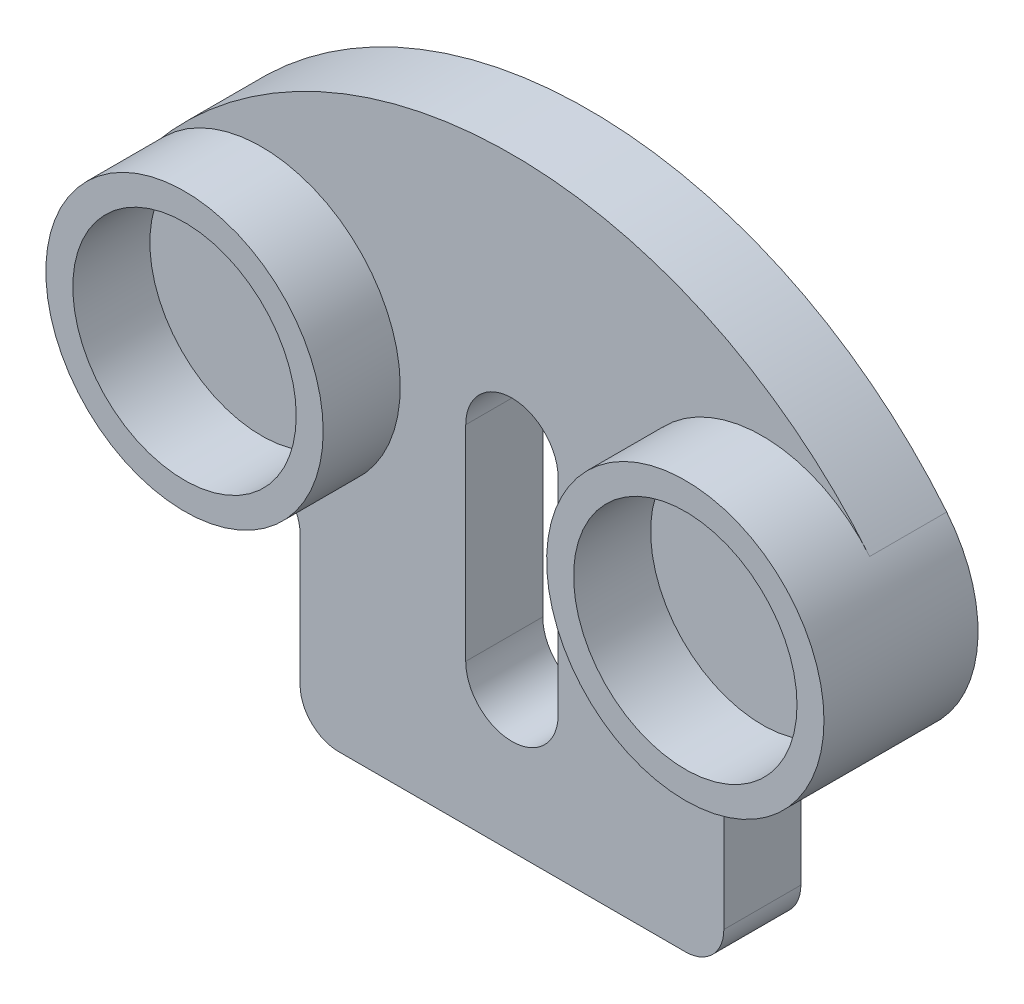
SolidWorks part; units mm, degrees
ref_plane "Płaszczyzna przednia" through (0, 0, 0) normal (0, 0, 1) x (1, 0, 0)
ref_plane "Płaszczyzna górna" through (0, 0, 0) normal (0, 1, 0) x (1, 0, 0)
ref_plane "Płaszczyzna prawa" through (0, 0, 0) normal (1, 0, 0) x (0, 0, -1)
sketch "Szkic1" plane through (0, 0, 0) normal (0, 0, 1) x (1, 0, 0)
  line L0 (-6, 26.6036) -> (-6, 0)
  line L1 (6, 26.6036) -> (6, 0)
  line L2 (-22.5, -18.3964) -> (22.5, -18.3964)
  line L3 (0, 0) -> (0, -18.3964) construction
  line L4 (-95.3968, 26.6036) -> (116.5066, 26.6036) construction
  line L5 (-27.5, -13.3964) -> (-27.5, 3.6036)
  line L6 (27.5, -13.3964) -> (27.5, 3.6036)
  circle A2 centre (0, 0) radius 6
  circle A4 centre (0, 26.6036) radius 6
  circle A5 centre (-32.5, 26.6036) radius 18
  circle A6 centre (32.5, 26.6036) radius 18
  circle A7 centre (-32.5, 26.6036) radius 13
  circle A8 centre (32.5, 26.6036) radius 13
  arc A9 (-22.5, -18.3964) -> (-27.5, -13.3964) centre (-22.5, -13.3964) cw
  arc A10 (-27.5, 3.6036) -> (-32.5, 8.6036) centre (-32.5, 3.6036) ccw
  arc A11 (22.5, -18.3964) -> (27.5, -13.3964) centre (22.5, -13.3964) ccw
  arc A12 (27.5, 3.6036) -> (32.5, 8.6036) centre (32.5, 3.6036) cw
  arc A13 (-46.4286, 38.0051) -> (46.4286, 38.0051) centre (0, 0) cw
  point P35 (0, 0)
  dimension "D3" = 45
  dimension "D4" = 65
  dimension "D2" = 12
  dimension "D6" = 36
  dimension "D7" = 32.5
  dimension "D8" = 5
  dimension "D1" = 12
  dimension "D5" = 36
  dimension "D10" = 5
  dimension "D11" = 5
  dimension "D12" = 5
  dimension "D13" = 5
  dimension "D14" = 60
  dimension "D9" = 5
  dimension "D15" = 45
extrude "Dodanie-wyciągnięcie5" add sketch "Szkic1" along normal blind 20 contours A13 A5 A10 L5 A9 L2 A11 L6 A12 A6 A4 L1 A2 L0 | A5 A7 | A8 | A6 A8 | A7
sketch "Szkic3" plane through (0, 0, 20) normal (0, 0, 1) x (1, 0, 0)
  line L3 (-27.5, 3.6036) -> (-27.5, -13.3964)
  line L4 (-22.5, -18.3964) -> (22.5, -18.3964)
  line L5 (27.5, -13.3964) -> (27.5, 3.6036)
  line L6 (-27.5, 3.6036) -> (-27.5, -13.3964)
  line L7 (-22.5, -18.3964) -> (22.5, -18.3964)
  line L8 (27.5, -13.3964) -> (27.5, 3.6036)
  circle A0 centre (-32.5, 26.6036) radius 14.5
  circle A1 centre (32.5, 26.6036) radius 14.5
  circle A2 centre (-32.5, 26.6036) radius 18
  circle A3 centre (32.5, 26.6036) radius 18
  arc A7 (46.4286, 38.0051) -> (-46.4286, 38.0051) centre (0, 0) ccw
  arc A8 (-46.4286, 38.0051) -> (-32.5, 8.6036) centre (-32.5, 26.6036) ccw
  arc A9 (-27.5, 3.6036) -> (-32.5, 8.6036) centre (-32.5, 3.6036) ccw
  arc A10 (-27.5, -13.3964) -> (-22.5, -18.3964) centre (-22.5, -13.3964) ccw
  arc A11 (22.5, -18.3964) -> (27.5, -13.3964) centre (22.5, -13.3964) ccw
  arc A12 (32.5, 8.6036) -> (27.5, 3.6036) centre (32.5, 3.6036) ccw
  arc A13 (32.5, 8.6036) -> (46.4286, 38.0051) centre (32.5, 26.6036) ccw
  arc A14 (46.4286, 38.0051) -> (-46.4286, 38.0051) centre (0, 0) ccw
  arc A15 (-46.4286, 38.0051) -> (-32.5, 8.6036) centre (-32.5, 26.6036) ccw
  arc A16 (-27.5, 3.6036) -> (-32.5, 8.6036) centre (-32.5, 3.6036) ccw
  arc A17 (-27.5, -13.3964) -> (-22.5, -18.3964) centre (-22.5, -13.3964) ccw
  arc A18 (22.5, -18.3964) -> (27.5, -13.3964) centre (22.5, -13.3964) ccw
  arc A19 (32.5, 8.6036) -> (27.5, 3.6036) centre (32.5, 3.6036) ccw
  arc A20 (32.5, 8.6036) -> (46.4286, 38.0051) centre (32.5, 26.6036) ccw
  arc M13 (46.4286, 38.0051) -> (-46.4286, 38.0051) centre (0, 0) ccw
  arc M15 (-32.5, 8.6036) -> (-27.5, 3.6036) centre (-32.5, 3.6036) cw
  line M16 (-27.5, 3.6036) -> (-27.5, -13.3964)
  arc M17 (-27.5, -13.3964) -> (-22.5, -18.3964) centre (-22.5, -13.3964) ccw
  line M18 (-22.5, -18.3964) -> (22.5, -18.3964)
  arc M19 (22.5, -18.3964) -> (27.5, -13.3964) centre (22.5, -13.3964) ccw
  line M20 (27.5, -13.3964) -> (27.5, 3.6036)
  arc M21 (27.5, 3.6036) -> (32.5, 8.6036) centre (32.5, 3.6036) cw
  arc M23 (-6, 26.6036) -> (6, 26.6036) centre (0, 26.6036) cw
  line M24 (6, 26.6036) -> (6, 0)
  arc M25 (6, 0) -> (-6, 0) centre (0, 0) cw
  line M26 (-6, 0) -> (-6, 26.6036)
  dimension "D2" = 29
  dimension "D3" = 29
  dimension "D4" = 36
  dimension "D5" = 36
  dimension "D1" = 0
extrude "Wytnij-wyciągnięcie1" cut sketch "Szkic3" against normal blind 10 contours A3 A2 M13 M15 M16 M17 M18 M19 M20 M21 M26 M23 M24 M25 | A0 | A1
